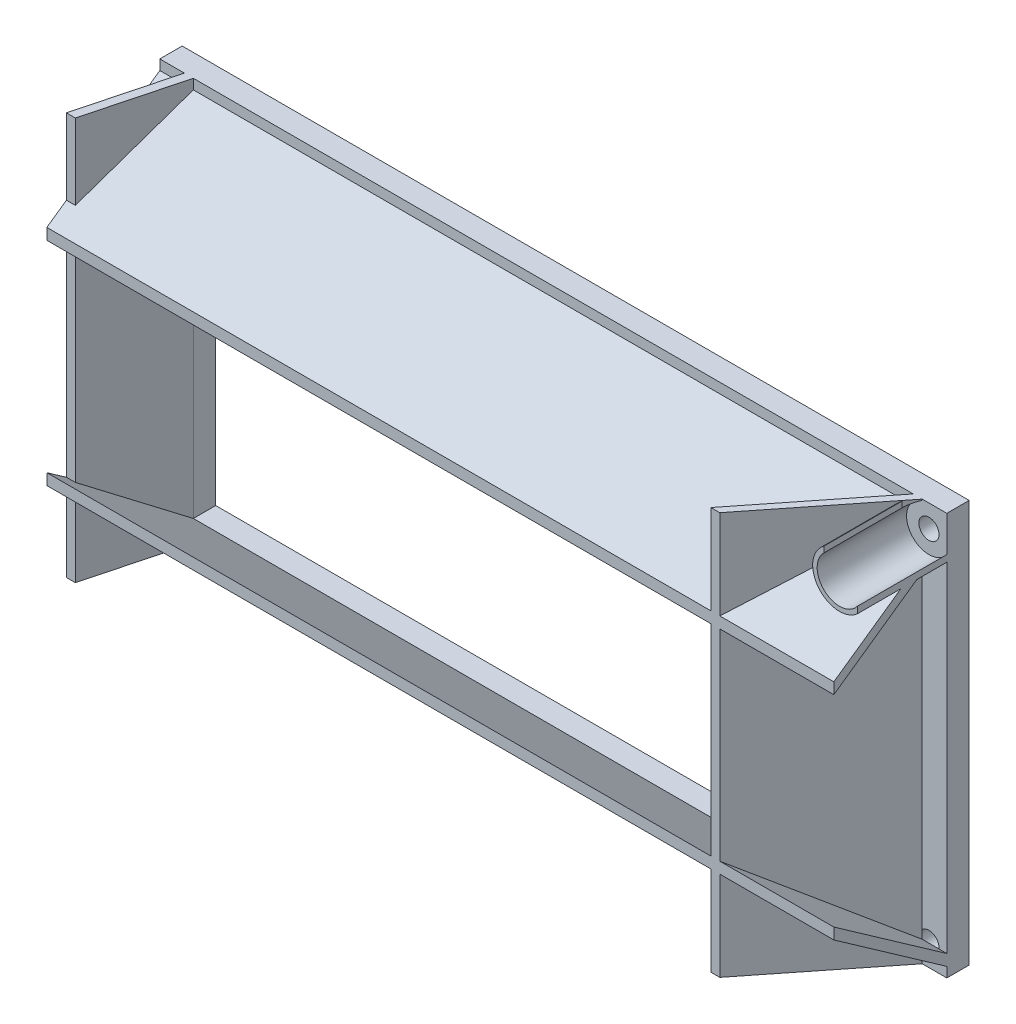
SolidWorks part; units mm, degrees
ref_plane "Front Plane" through (0, 0, 0) normal (0, 0, 1) x (1, 0, 0)
ref_plane "Top Plane" through (0, 0, 0) normal (0, 1, 0) x (1, 0, 0)
ref_plane "Right Plane" through (0, 0, 0) normal (1, 0, 0) x (0, 0, -1)
sketch "Sketch1" plane through (0, 0, 0) normal (0, 0, 1) x (1, 0, 0)
  line L1 (-88, -45) -> (88, -45)
  line L2 (-88, -45) -> (-88, 45)
  line L3 (-88, 45) -> (88, 45)
  line L4 (88, -45) -> (88, 45)
  line L5 (-88, -45) -> (88, 45) construction
  line L6 (-88, 45) -> (88, -45) construction
  line L7 (-80.5, -40.25) -> (80.5, -40.25)
  line L8 (-80.5, -40.25) -> (-80.5, 40.25)
  line L9 (-80.5, 40.25) -> (80.5, 40.25)
  line L10 (80.5, -40.25) -> (80.5, 40.25)
  line L11 (-80.5, -40.25) -> (80.5, 40.25) construction
  line L12 (-80.5, 40.25) -> (80.5, -40.25) construction
  point P0 (0, 0)
  point P6 (0, 0)
  dimension "D1" = 176
  dimension "D2" = 90
  dimension "D3" = 161
  dimension "D4" = 80.5
extrude "Boss-Extrude1" add sketch "Sketch1" along normal blind 5
hole_wizard "M4 Clearance Hole1" positions "Sketch2" profile "Sketch4" hole size "M4" standard "ANSI Metric" end condition through all
sketch "Sketch2" plane through (0, 0, 5) normal (0, 0, 1) x (1, 0, 0)
  line L1 (-84, -40) -> (84, -40)
  line L2 (-84, -40) -> (-84, 40)
  line L3 (-84, 40) -> (84, 40)
  line L4 (84, -40) -> (84, 40)
  line L5 (-84, -40) -> (84, 40) construction
  line L6 (-84, 40) -> (84, -40) construction
  point P2 (84, 40)
  point P157 (-84, -40)
  point P158 (-84, 40)
  point P159 (84, -40)
  dimension "D1" = 168
  dimension "D2" = 80
sketch "Sketch4" plane through (84, 40, 5) normal (1, 0, 0) x (0, -1, 0)
  line L0 (0, 0) -> (0, 5)
  line L1 (0, 5) -> (2.25, 5)
  line L2 (2.25, 5) -> (2.25, 0)
  line L5 (2.25, 0) -> (0, 0)
  line L11 (0, -6.35) -> (0, 107.95) construction
  dimension "Thru Hole Dia." = 4.5
  dimension "Thru Hole Depth" = 5
sketch "Sketch7" plane through (0, 45, 0) normal (0, 1, 0) x (1, 0, 0)
  line L0 (-82.5, -5) -> (-88, -25.8866)
  line L1 (88, -5) -> (-88, -5) construction
  line L2 (-88, -25.8866) -> (-86, -25.8866)
  line L3 (-86, -25.8866) -> (-80.5, -5)
  line L4 (80.5, -5) -> (60.5, -30.2643)
  line L5 (60.5, -30.2643) -> (62.5, -30.2643)
  line L6 (62.5, -30.2643) -> (82.5, -5)
  line L7 (88, -5) -> (88, 0) construction
  line L8 (82.5, -5) -> (80.5, -5)
  line L9 (-82.5, -5) -> (-80.5, -5)
  point P13 (0, 0)
  dimension "D1" = 2
  dimension "D2" = 7.5
  dimension "D3" = 2
  dimension "D4" = 7.5
  dimension "D5" = 20
extrude "Boss-Extrude2" add sketch "Sketch7" against normal up to vertex (90 mm away) up to point (88, -45, 5)
sketch "Sketch8" plane through (88, 0, 0) normal (1, 0, 0) x (0, 0, -1)
  line L0 (-5, 40.25) -> (-30.2643, 22.5)
  line L1 (-30.2643, -45) -> (-30.2643, 45) construction
  line L2 (-30.2643, 22.5) -> (-30.2643, 25)
  line L3 (-30.2643, 25) -> (-5, 42.75)
  line L4 (-5, 42.75) -> (-5, 40.25)
  line L5 (-5, -45) -> (-5, 45) construction
  line L6 (-5, 45) -> (0, 45) construction
  dimension "D1" = 2.5
  dimension "D2" = 4.75
  dimension "D3" = 20
extrude "Boss-Extrude11" add sketch "Sketch8" against normal blind 176 separate body
mirror "Mirror2" about plane through (0, 0, 0) normal (0, 1, 0) of bodies 104
combine bodies "Combine2" operation type add bodies to combine 104 105 103
sketch "Sketch9" plane through (0, 0, 5) normal (0, 0, 1) x (1, 0, 0)
  line L0 (16.6454, 0) -> (-16.6454, 0) construction
  line L1 (-84, -40) -> (84, -40)
  line L2 (-84, -40) -> (-84, 40)
  line L3 (-84, 40) -> (84, 40)
  line L4 (84, -40) -> (84, 40)
  line L5 (-84, -40) -> (84, 40) construction
  line L6 (-84, 40) -> (84, -40) construction
  line L7 (0, -16.6454) -> (0, 16.6454) construction
  circle A0 centre (84, 40) radius 5
  circle A1 centre (84, -40) radius 5
  circle A2 centre (-84, -40) radius 5
  circle A3 centre (-84, 40) radius 5
  point P0 (0, 0)
  line M5 (88, 40.25) -> (86.2361, 40.25)
  arc M6 (86.2361, 40.25) -> (82.5, 38.3229) centre (84, 40) cw
  line M7 (82.5, 38.3229) -> (82.5, -38.3229)
  line M10 (88, -40.25) -> (88, 40.25)
  dimension "D3" = 10
  dimension "D1" = 80
  dimension "D2" = 168
extrude "Cut-Extrude1" cut sketch "Sketch9" along normal blind 20 contours L4 A0 M10 M5 M6 | A0 L3 L4 M10 M6 M5 | L3 A0 L4 M7 M6 | A0 L4 M7 M6
sketch "Sketch10" plane through (0, 0, 5) normal (0, 0, 1) x (1, 0, 0)
  line L0 (88, 45) -> (88, 35.5279)
  line L1 (88, -40.25) -> (88, 45) construction
  line L2 (88, 45) -> (79.6071, 45)
  line L3 (80.5, 45) -> (-80.5, 45) construction
  circle A0 centre (84, 40) radius 5
  circle A1 centre (84, 40) radius 6
  line M4 (88, -40.25) -> (88, 45)
  line M8 (80.5, 43.5707) -> (80.5, 45)
  line M11 (-80.5, 42.75) -> (79.8242, 42.75)
  arc M12 (79.8242, 42.75) -> (79.0063, 40.25) centre (84, 40) ccw
  arc M15 (80.5, 36.4293) -> (82.5, 35.2303) centre (84, 40) ccw
  line M16 (82.5, 35.2303) -> (82.5, -38.3229)
  dimension "D1" = 12
extrude "Boss-Extrude12" add sketch "Sketch10" along normal blind 20 contours A1 A0 M16 M4 | A1 A0 M11 M16 M15 M12 | A1 A0 M8 M11
sketch "Sketch11" plane through (0, 0, 5) normal (0, 0, 1) x (1, 0, 0)
  line L0 (80.5, 40.25) -> (80.5, 35.1266)
  line L1 (80.5, 40.25) -> (78.0052, 40.25)
  circle A0 centre (84, 40) radius 6
  line M7 (79.0063, 40.25) -> (80.5, 40.25)
  line M8 (80.5, 40.25) -> (80.5, 36.4293)
extrude "Boss-Extrude13" add sketch "Sketch11" against normal blind 5 contours L1 A0 L0 M8 M7
